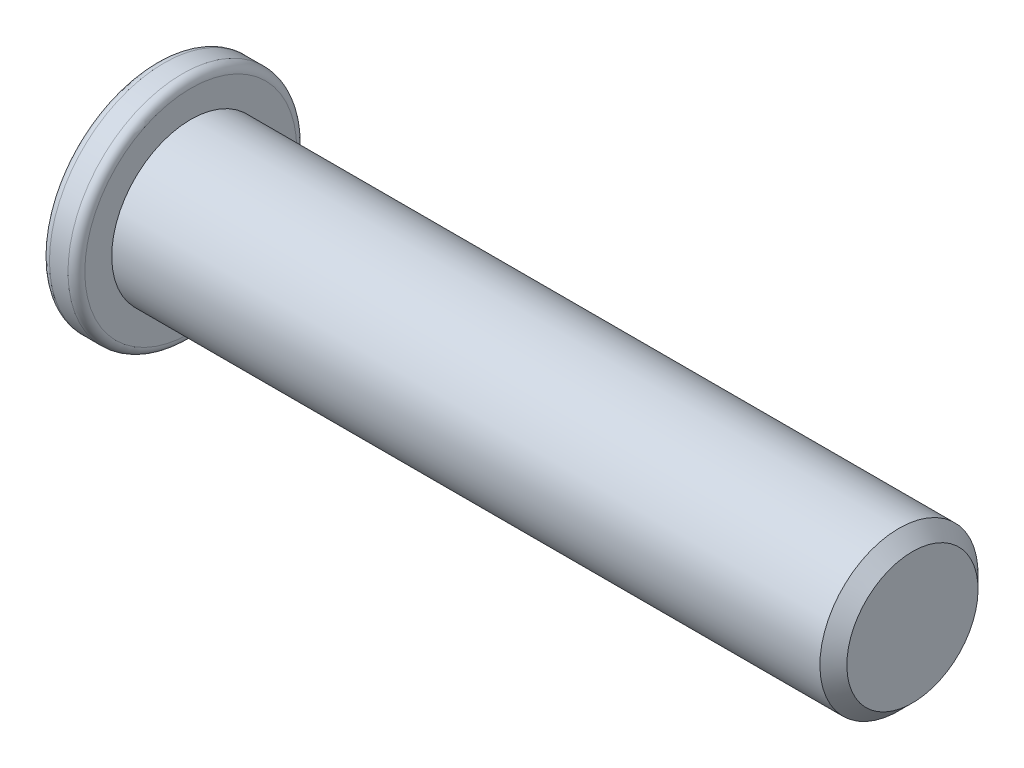
SolidWorks part; units mm, degrees
material "1060 Alloy"
ref_plane "Front Plane" through (0, 0, 0) normal (0, 0, 1) x (1, 0, 0)
ref_plane "Top Plane" through (0, 0, 0) normal (0, 1, 0) x (1, 0, 0)
ref_plane "Right Plane" through (0, 0, 0) normal (1, 0, 0) x (0, 0, -1)
sketch "Sketch1" plane through (0, 0, 0) normal (0, 0, 1) x (1, 0, 0)
  line L0 (0, 0) -> (0, 6.8)
  line L1 (0, 6.8) -> (2.1, 6.8)
  line L2 (2.1, 6.8) -> (2.1, 4.7)
  line L3 (2.1, 4.7) -> (45, 4.7)
  line L4 (45, 4.7) -> (45, 0)
  line L5 (45, 0) -> (0, 0)
  dimension "D1" = 2.1
  dimension "D2" = 6.8
  dimension "D3" = 45
  dimension "D4" = 4.7
revolve "Revolve1" add sketch "Sketch1" angle 360 about L5
cosmetic thread "Cosmetic Thread1" parameters "D1"=19.5, "D2"=6.891
fillet "Fillet1" radius 0.5 2 edges at (2.1, 6.8, 0) (0, 6.8, 0)
chamfer "Chamfer1" distance 0.8 angle 45 1 edges at (45, 4.7, 0)
